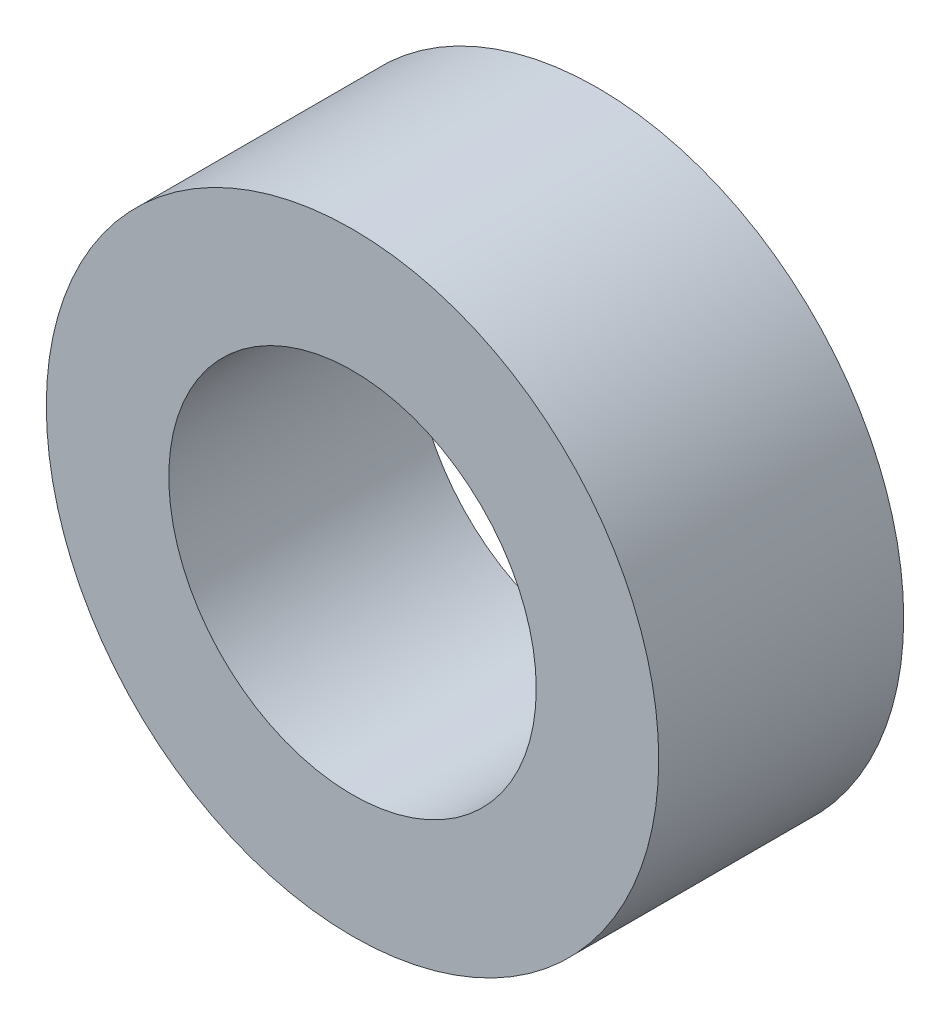
SolidWorks part; units mm, degrees
material "ABS"
ref_plane "Front Plane" through (0, 0, 0) normal (0, 0, 1) x (1, 0, 0)
ref_plane "Top Plane" through (0, 0, 0) normal (0, 1, 0) x (1, 0, 0)
ref_plane "Right Plane" through (0, 0, 0) normal (1, 0, 0) x (0, 0, -1)
sketch "Sketch1" plane through (0, 0, 0) normal (0, 0, 1) x (1, 0, 0)
  circle A0 centre (0, 0) radius 4.5
  circle A1 centre (0, 0) radius 7.5
  dimension "D1" = 15
  dimension "D2" = 9
extrude "Boss-Extrude1" add sketch "Sketch1" along normal blind 6
